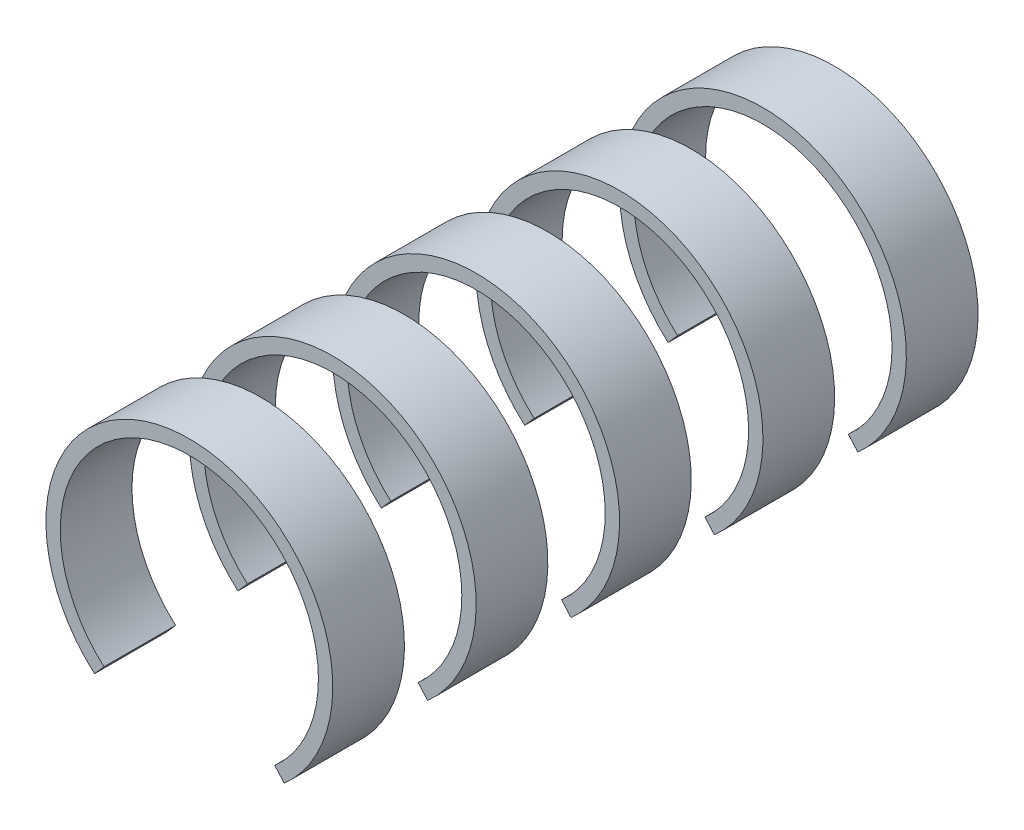
SolidWorks part; units mm, degrees
ref_plane "Front Plane" through (0, 0, 0) normal (0, 0, 1) x (1, 0, 0)
ref_plane "Top Plane" through (0, 0, 0) normal (0, 1, 0) x (1, 0, 0)
ref_plane "Right Plane" through (0, 0, 0) normal (1, 0, 0) x (0, 0, -1)
sketch "Sketch2" plane through (0, 0, 0) normal (0, 0, 1) x (1, 0, 0)
  line L0 (-1220, 3) -> (1220, 3) construction
  line L1 (-1220, 0) -> (1220, 0) construction
  arc A0 (-66.1438, 3) -> (66.1438, 3) centre (0, 78) cw
  point P7 (0, 0)
  dimension "D1" = 100
  dimension "D2" = 75
extrude "Extrude-Thin1" add sketch "Sketch2" against normal blind 50 from offset 350 thin offset against normal yes
pattern_linear "LPattern1" count 5 spacing 100 along (0, 0, -1) of "Extrude-Thin1"
